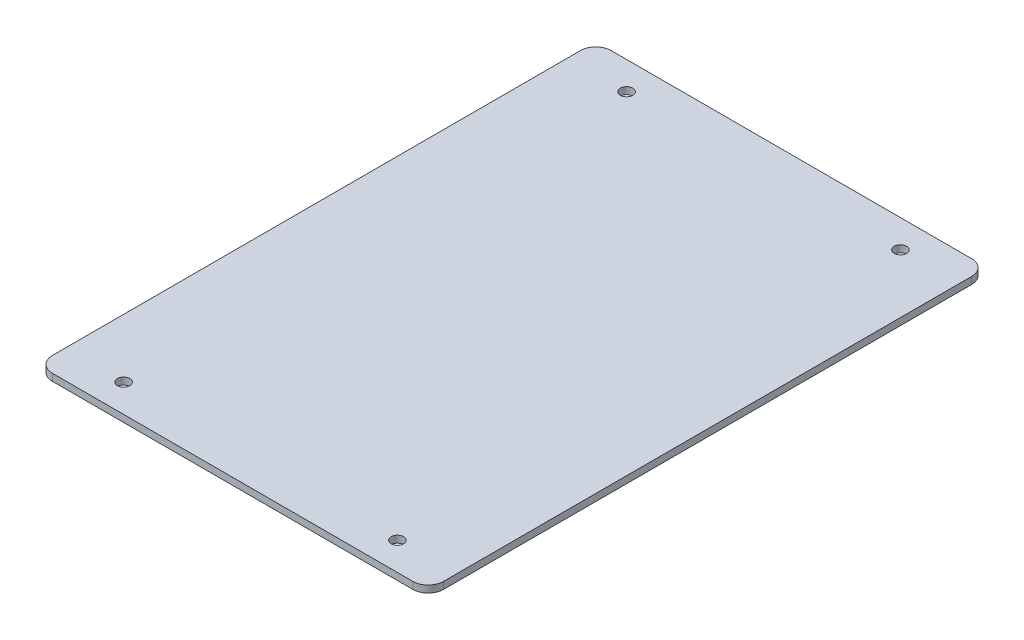
SolidWorks part; units mm, degrees
material "PVC 0.007 Plasticized"
ref_plane "Front Plane" through (0, 0, 0) normal (0, 0, 1) x (1, 0, 0)
ref_plane "Top Plane" through (0, 0, 0) normal (0, 1, 0) x (1, 0, 0)
ref_plane "Right Plane" through (0, 0, 0) normal (1, 0, 0) x (0, 0, -1)
sketch "Sketch1" plane through (0, 0, 0) normal (0, 1, 0) x (1, 0, 0)
  line L1 (-35.56, -50.8) -> (35.56, -50.8)
  line L2 (-35.56, -50.8) -> (-35.56, 50.8)
  line L3 (-35.56, 50.8) -> (35.56, 50.8)
  line L4 (35.56, -50.8) -> (35.56, 50.8)
  line L5 (-35.56, -50.8) -> (35.56, 50.8) construction
  line L6 (-35.56, 50.8) -> (35.56, -50.8) construction
  point P0 (0, 0)
  dimension "D1" = 71.12
  dimension "D2" = 101.6
extrude "Boss-Extrude1" add sketch "Sketch1" along normal blind 1.27
fillet "Fillet1" radius 2.794 4 edges at (35.56, 0.635, -50.8) (-35.56, 0.635, -50.8) (-35.56, 0.635, 50.8) (35.56, 0.635, 50.8)
sketch "Sketch2" plane through (0, 1.27, 0) normal (0, 1, 0) x (1, 0, 0)
  line L0 (32.766, 50.8) -> (-32.766, 50.8) construction
  line L1 (-35.56, 48.006) -> (-35.56, -48.006) construction
  line L2 (35.56, -48.006) -> (35.56, 48.006) construction
  line L3 (-32.766, -50.8) -> (32.766, -50.8) construction
  point P0 (-24.892, 45.72)
  point P5 (24.892, 45.72)
  point P8 (-24.892, -45.72)
  point P11 (24.892, -45.72)
  dimension "D1" = 5.08
  dimension "D2" = 10.668
  dimension "D3" = 10.668
  dimension "D4" = 10.668
  dimension "D5" = 5.08
  dimension "D6" = 10.668
hole_wizard "#4-40 Tapped Hole1" positions "Sketch2" profile "Sketch3" tap size "#4-40" standard "ANSI Inch"
sketch "Sketch3" plane through (-24.892, 1.27, -45.72) normal (1, 0, 0) x (0, 0, 1)
  line L0 (0, 0) -> (0, 2.9652)
  line L1 (0, 2.9652) -> (1.1303, 2.286)
  line L2 (1.1303, 2.286) -> (1.1303, 0)
  line L5 (1.1303, 0) -> (0, 0)
  line L10 (0, 2.9652) -> (-1.1303, 2.286) construction
  line L11 (0, -6.35) -> (0, 107.95) construction
  dimension "Tap Drill Dia." = 2.2606
  dimension "Tap Drill Depth" = 2.286
  dimension "Drill Angle" = 118
cosmetic thread "Hole Thread1" parameters "D1"=5.588, "D2"=2.8448
cosmetic thread "Hole Thread2" parameters "D1"=5.588, "D2"=2.8448
cosmetic thread "Hole Thread3" parameters "D1"=5.588, "D2"=2.8448
cosmetic thread "Hole Thread4" parameters "D1"=5.588, "D2"=2.8448
